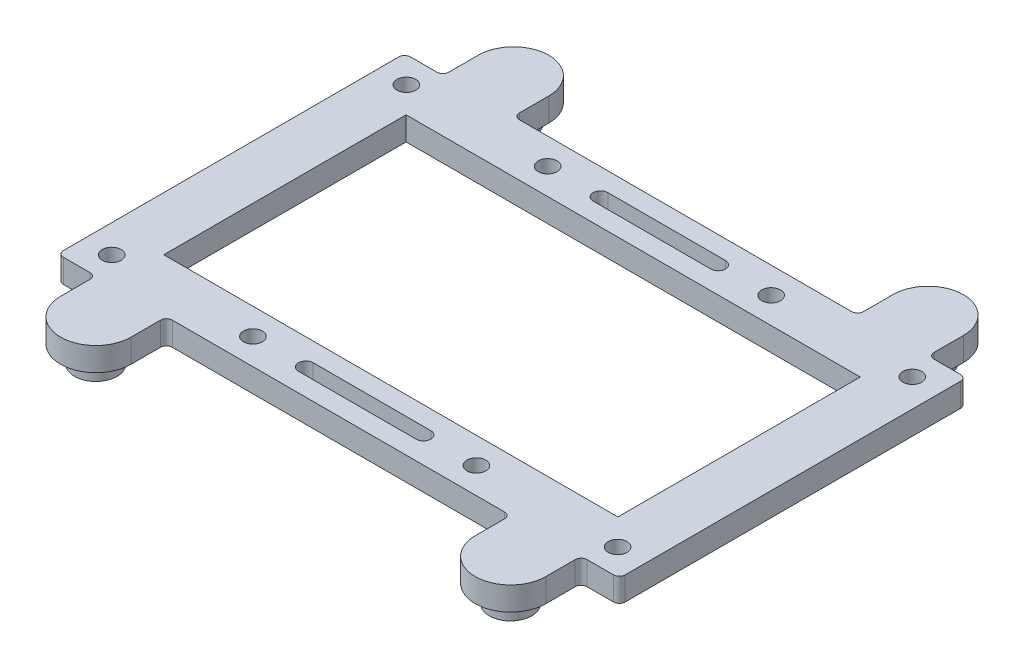
SolidWorks part; units mm, degrees
ref_plane "前视基准面" through (0, 0, 0) normal (0, 0, 1) x (1, 0, 0)
ref_plane "上视基准面" through (0, 0, 0) normal (0, 1, 0) x (1, 0, 0)
ref_plane "右视基准面" through (0, 0, 0) normal (1, 0, 0) x (0, 0, -1)
other "Configuration Table"
sketch "草图1" plane through (0, 0, 0) normal (0, 1, 0) x (1, 0, 0)
  line L0 (0, 35.4779) -> (0, -35.3561) construction
  line L1 (-47.75, 29.5) -> (-41.25, 29.5)
  line L2 (-47.75, 29.5) -> (-47.75, -29.5)
  line L3 (-47.75, -29.5) -> (-41.25, -29.5)
  line L4 (47.75, 29.5) -> (47.75, -29.5)
  line L5 (-47.75, 29.5) -> (47.75, -29.5) construction
  line L6 (-47.75, -29.5) -> (47.75, 29.5) construction
  line L9 (-41.25, 29.5) -> (-41.25, 35.5)
  line L11 (-29.25, 29.5) -> (-29.25, 35.5)
  line L12 (29.25, 29.5) -> (29.25, 35.5)
  line L14 (41.25, 29.5) -> (41.25, 35.5)
  line L15 (-78.7463, 0) -> (58.6748, 0) construction
  line L16 (41.25, -29.5) -> (41.25, -35.5)
  line L18 (29.25, -29.5) -> (29.25, -35.5)
  line L21 (-29.25, -29.5) -> (-29.25, -35.5)
  line L23 (-41.25, -29.5) -> (-41.25, -35.5)
  line L24 (-29.25, 29.5) -> (-3, 29.5)
  line L25 (41.25, 29.5) -> (47.75, 29.5)
  line L26 (41.25, -29.5) -> (47.75, -29.5)
  line L27 (-29.25, -29.5) -> (-3, -29.5)
  line L48 (3.25, 29.5) -> (29.25, 29.5)
  line L49 (3.25, -29.5) -> (29.25, -29.5)
  line L50 (-41.25, 35.5) -> (-29.25, 35.5) construction
  line L51 (-3, 29.5) -> (3.25, 29.5)
  line L52 (3.25, -29.5) -> (-3, -29.5)
  arc A16 (-29.25, 35.5) -> (-41.25, 35.5) centre (-35.25, 35.5) ccw
  arc A17 (29.25, 35.5) -> (41.25, 35.5) centre (35.25, 35.5) cw
  arc A18 (29.25, -35.5) -> (41.25, -35.5) centre (35.25, -35.5) ccw
  arc A19 (-29.25, -35.5) -> (-41.25, -35.5) centre (-35.25, -35.5) cw
  point P0 (0, 0)
  dimension "D10" = 71
  dimension "D1" = 95.5
  dimension "D2" = 58.5
  dimension "D4" = 12
  dimension "D5" = 6
extrude "凸台-拉伸1" add sketch "草图1" against normal blind 4
sketch "草图3" plane through (0, -4, 0) normal (0, -1, 0) x (1, 0, 0)
  line L0 (47.75, 29.5) -> (47.75, -29.5) construction
  line L1 (-45.25, -27) -> (45.25, -27)
  line L2 (-45.25, -27) -> (-45.25, 27)
  line L3 (-45.25, 27) -> (45.25, 27)
  line L4 (45.25, -27) -> (45.25, 27)
  line L5 (-45.25, -27) -> (45.25, 27) construction
  line L6 (-45.25, 27) -> (45.25, -27) construction
  line L7 (-29.25, 29.5) -> (29.25, 29.5) construction
  point P0 (0, 0)
  dimension "D1" = 2.5
  dimension "D2" = 2.5
sketch "草图4" plane through (0, -4, 0) normal (0, -1, 0) x (1, 0, 0)
  line L1 (-71.7869, 0) -> (71.1524, 0) construction
  line L2 (0, 61.1393) -> (0, -47.8922) construction
  circle A4 centre (-35.25, 35.5) radius 3.6
  circle A5 centre (-35.25, -35.5) radius 3.6
  circle A6 centre (35.25, -35.5) radius 3.6
  circle A7 centre (35.25, 35.5) radius 3.6
extrude "凸台-拉伸2" add sketch "草图4" along normal blind 3 separate body
sketch "草图5" plane through (0, -7, 0) normal (0, -1, 0) x (1, 0, 0)
  line L0 (-58.868, 0) -> (56.1189, 0) construction
  line L1 (0, 46.5823) -> (0, -51.4835) construction
  circle A0 centre (-35.25, 35.5) radius 1.8
  circle A4 centre (-35.25, -35.5) radius 1.8
  circle A5 centre (35.25, -35.5) radius 1.8
  circle A6 centre (35.25, 35.5) radius 1.8
extrude "凸台-拉伸3" add sketch "草图5" along normal blind 1.3 separate body
sketch "草图6" plane through (0, -4, 0) normal (0, -1, 0) x (1, 0, 0)
  line L0 (-29.25, 29.5) -> (29.25, 29.5) construction
  line L1 (-47.5, 29.5) -> (47.5, 29.5)
  line L2 (-47.5, 29.5) -> (-47.5, -29.5)
  line L3 (-47.5, -29.5) -> (47.5, -29.5)
  line L4 (47.5, 29.5) -> (47.5, -29.5)
  line L5 (29.25, -29.5) -> (-29.25, -29.5) construction
sketch "草图10" plane through (0, 0, 0) normal (0, 1, 0) x (1, 0, 0)
  line L5 (38.6, 20.6) -> (-38.6, 20.6)
  line L6 (38.6, 20.6) -> (38.6, -20.6)
  line L7 (38.6, -20.6) -> (-38.6, -20.6)
  line L8 (-38.6, 20.6) -> (-38.6, -20.6)
  line L9 (38.6, 20.6) -> (-38.6, -20.6) construction
  line L10 (38.6, -20.6) -> (-38.6, 20.6) construction
  point P0 (0, 0)
  dimension "D1" = 77.2
  dimension "D2" = 41.2
extrude "切除-拉伸5" cut sketch "草图10" against normal through all
sketch "草图16" plane through (0, 0, 0) normal (0, 1, 0) x (1, 0, 0)
  line L0 (-10, 25.05) -> (10, 25.05) construction
  line L1 (-10, 26.3) -> (10, 26.3)
  line L2 (-10, 23.8) -> (10, 23.8)
  line L3 (-1000, 0) -> (49000, 0) construction
  line L4 (0, -1000) -> (0, 49000) construction
  line L5 (29.25, 29.5) -> (-29.25, 29.5) construction
  line L6 (-10, -25.05) -> (10, -25.05) construction
  line L7 (-10, -26.3) -> (10, -26.3)
  line L8 (-10, -23.8) -> (10, -23.8)
  arc A0 (-10, 26.3) -> (-10, 23.8) centre (-10, 25.05) ccw
  arc A1 (10, 23.8) -> (10, 26.3) centre (10, 25.05) ccw
  arc A2 (-10, -26.3) -> (-10, -23.8) centre (-10, -25.05) cw
  arc A3 (10, -23.8) -> (10, -26.3) centre (10, -25.05) cw
  circle A4 centre (19, 25.05) radius 1.6
  circle A5 centre (43, 25.05) radius 1.6
  circle A6 centre (-43, 25.05) radius 1.6
  circle A7 centre (-19, 25.05) radius 1.6
  circle A8 centre (43, -25.05) radius 1.6
  circle A9 centre (19, -25.05) radius 1.6
  circle A10 centre (-19, -25.05) radius 1.6
  circle A11 centre (-43, -25.05) radius 1.6
  point P2 (0, 25.05)
  point P17 (0, -25.05)
  point P27 (0, 23.05)
  dimension "D4" = 3.2
  dimension "D5" = 3.2
  dimension "D1" = 2.5
  dimension "D2" = 20
  dimension "D3" = 4.45
  dimension "D6" = 4.45
  dimension "D7" = 9
  dimension "D8" = 24
extrude "切除-拉伸6" cut sketch "草图16" against normal blind 10
fillet "圆角1" radius 1 12 edges at (-29.25, -2, -29.5) (-41.25, -2, -29.5) (29.25, -2, -29.5) (41.25, -2, -29.5) (29.25, -2, 29.5) (41.25, -2, 29.5) (-29.25, -2, 29.5) (-41.25, -2, 29.5) (-47.75, -2, 29.5) (-47.75, -2, -29.5) (47.75, -2, 29.5) (47.75, -2, -29.5)
sketch "草图14" plane through (0, -3, 0) normal (0, -1, 0) x (1, 0, 0)
  line L0 (4.73, 0) -> (-4.73, 0) construction
  line L1 (-42, 24) -> (-37, 24)
  line L2 (-42, 24) -> (-42, 20)
  line L3 (-42, 20) -> (-37, 20)
  line L4 (-37, 24) -> (-37, 20)
  line L5 (-42, 24) -> (-37, 20) construction
  line L6 (-42, 20) -> (-37, 24) construction
  line L7 (-42, -20) -> (-37, -20)
  line L8 (-37, -24) -> (-37, -20)
  line L9 (-42, -24) -> (-37, -24)
  line L10 (-42, -24) -> (-42, -20)
  line L11 (0, -4.73) -> (0, 4.73) construction
  line L12 (42, -24) -> (42, -20)
  line L13 (42, -24) -> (37, -24)
  line L14 (37, -24) -> (37, -20)
  line L15 (42, -20) -> (37, -20)
  line L16 (42, 20) -> (37, 20)
  line L17 (37, 24) -> (37, 20)
  line L18 (42, 24) -> (37, 24)
  line L19 (42, 24) -> (42, 20)
  point P0 (-39.5, 22)
  dimension "D1" = 22
  dimension "D2" = 5
  dimension "D3" = 4
sketch "草图15" plane through (0, -3, 0) normal (0, -1, 0) x (1, 0, 0)
  line L0 (-45, 23) -> (32, 23) construction
  line L1 (-41, 20) -> (41, 20)
  line L2 (-41, 20) -> (-41, 16)
  line L3 (-41, 16) -> (41, 16)
  line L4 (41, 20) -> (41, 16)
  line L5 (-41, 20) -> (41, 16) construction
  line L6 (-41, 16) -> (41, 20) construction
  line L7 (4.73, 0) -> (-4.73, 0) construction
  line L8 (-41, -16) -> (41, -16)
  line L9 (41, -20) -> (41, -16)
  line L10 (-41, -20) -> (41, -20)
  line L11 (-41, -20) -> (-41, -16)
  line L12 (0, -4.73) -> (0, 4.73) construction
  line L13 (-40.75, 10) -> (-38.25, 10)
  line L14 (-40.75, 10) -> (-40.75, -10)
  line L15 (-40.75, -10) -> (-38.25, -10)
  line L16 (-38.25, 10) -> (-38.25, -10)
  line L17 (-40.75, 10) -> (-38.25, -10) construction
  line L18 (-40.75, -10) -> (-38.25, 10) construction
  line L19 (40.75, -10) -> (38.25, -10)
  line L20 (38.25, 10) -> (38.25, -10)
  line L21 (40.75, 10) -> (38.25, 10)
  line L22 (40.75, 10) -> (40.75, -10)
  point P0 (0, 18)
  point P5 (-39.5, 0)
  dimension "D1" = 4
  dimension "D2" = 5
  dimension "D3" = 82
  dimension "D4" = 2.5
  dimension "D5" = 20
